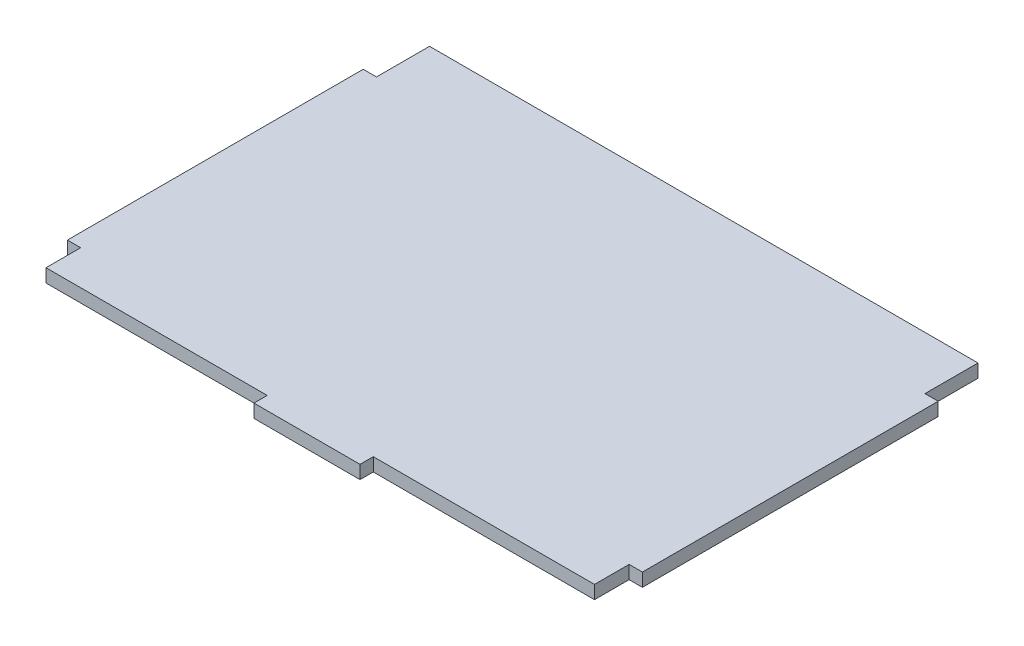
SolidWorks part; units mm, degrees
ref_plane "Front Plane" through (0, 0, 0) normal (0, 0, 1) x (1, 0, 0)
ref_plane "Top Plane" through (0, 0, 0) normal (0, 1, 0) x (1, 0, 0)
ref_plane "Right Plane" through (0, 0, 0) normal (1, 0, 0) x (0, 0, -1)
sketch "Sketch1" plane through (0, 0, 0) normal (0, 1, 0) x (1, 0, 0)
  line L0 (-68.834, 31.623) -> (-68.834, -47.498) construction
  line L2 (-65.659, -39.2028) -> (-65.659, -47.498)
  line L3 (-65.659, -47.498) -> (-12.7, -47.498)
  line L4 (65.659, -39.2028) -> (65.659, -47.498)
  line L5 (68.834, 31.623) -> (68.834, -47.498) construction
  line L6 (-65.659, -50.673) -> (65.659, -50.673) construction
  line L7 (-65.659, -39.2028) -> (-68.834, -39.2028)
  line L8 (-68.834, -39.2028) -> (-68.834, 31.623)
  line L9 (-65.659, 44.323) -> (65.659, 44.323)
  line L10 (-12.7, -47.498) -> (-12.7, -50.673)
  line L11 (-12.7, -50.673) -> (12.7, -50.673)
  line L12 (12.7, -50.673) -> (12.7, -47.498)
  line L13 (65.659, -39.2028) -> (68.834, -39.2028)
  line L14 (68.834, -39.2028) -> (68.834, 31.623)
  line L16 (12.7, -47.498) -> (65.659, -47.498)
  line L17 (-65.659, -39.2028) -> (-65.659, 47.498) construction
  line L18 (65.659, -39.2028) -> (65.659, 47.498) construction
  line L19 (-68.834, 31.623) -> (-65.659, 31.623)
  line L20 (-65.659, 44.323) -> (-65.659, 31.623)
  line L21 (68.834, 31.623) -> (65.659, 31.623)
  line L22 (65.659, 31.623) -> (65.659, 44.323)
  dimension "D1" = 94.996
  dimension "D2" = 131.318
  dimension "D3" = 3.175
  dimension "D4" = 3.175
  dimension "D5" = 3.175
  dimension "D6" = 70.8258
  dimension "D7" = 70.8258
  dimension "D8" = 25.4
  dimension "D9" = 52.959
  dimension "D11" = 12.7
  dimension "D12" = 12.7
  dimension "D13" = 70.8258
  dimension "D14" = 70.8258
extrude "Boss-Extrude3" add sketch "Sketch1" along normal blind 3.175
